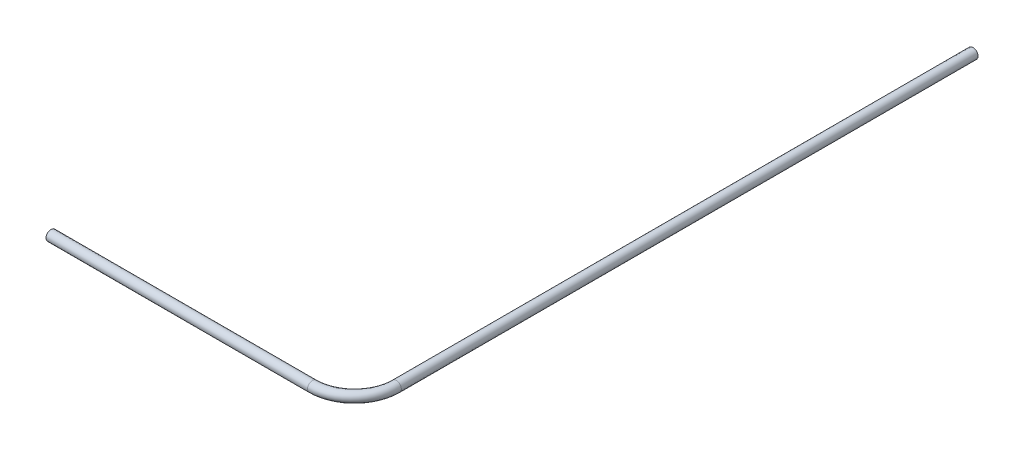
SolidWorks part; units mm, degrees
material "AISI 1020"
ref_plane "Спереди" through (0, 0, 0) normal (0, 0, 1) x (1, 0, 0)
ref_plane "Сверху" through (0, 0, 0) normal (0, 1, 0) x (1, 0, 0)
ref_plane "Справа" through (0, 0, 0) normal (1, 0, 0) x (0, 0, -1)
sketch "Эскиз1" plane through (0, 0, 0) normal (0, 1, 0) x (1, 0, 0)
  line L0 (12, 0) -> (12, -688)
  line L1 (-38, -738) -> (-350, -738)
  line L2 (6, -250) -> (6, 250) construction
  line L4 (-100, -744) -> (-600, -744) construction
  line L5 (-100, -756) -> (-100, -744) construction
  arc A0 (12, -688) -> (-38, -738) centre (-38, -688) cw
  dimension "D3" = 50
  dimension "D1" = 6
  dimension "D2" = 6
  dimension "D4" = 250
sketch "Эскиз2" plane through (0, 0, 0) normal (0, 0, 1) x (1, 0, 0)
  circle A0 centre (12, 0) radius 6
  dimension "D1" = 12
sweep "По траектории1" add profiles "Эскиз2" path "Эскиз1"
